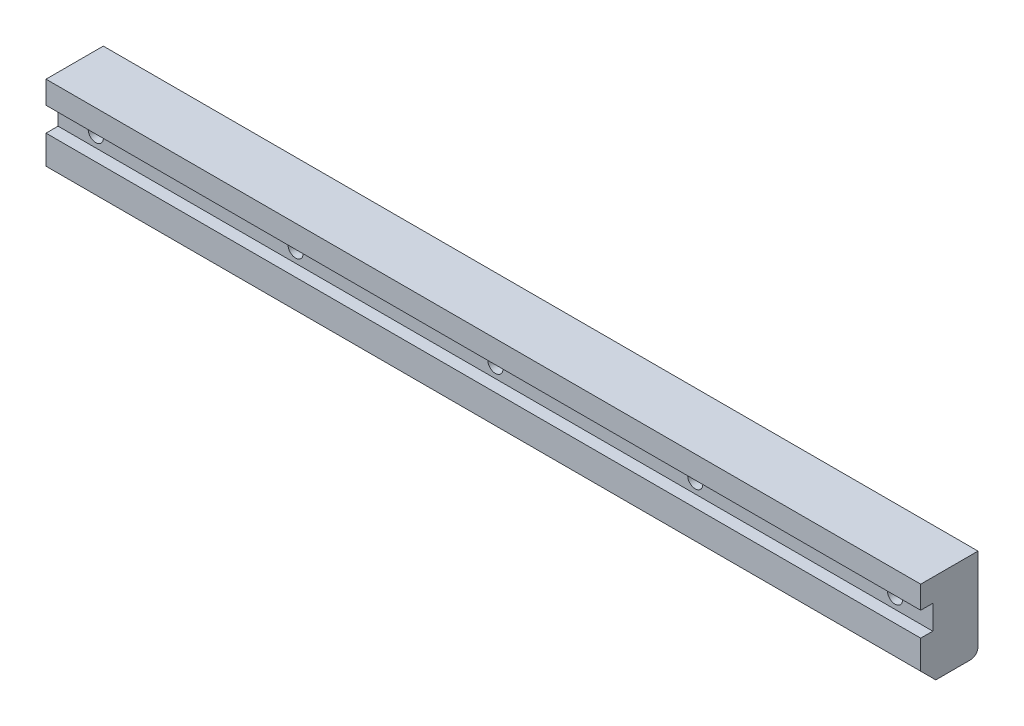
SolidWorks part; units mm, degrees
ref_plane "Alzado" through (0, 0, 0) normal (0, 0, 1) x (1, 0, 0)
ref_plane "Planta" through (0, 0, 0) normal (0, 1, 0) x (1, 0, 0)
ref_plane "Vista lateral" through (0, 0, 0) normal (1, 0, 0) x (0, 0, -1)
sketch "Croquis1" plane through (0, 0, 0) normal (1, 0, 0) x (0, 0, -1)
  line L0 (10, 0) -> (0, 10)
  line L1 (0, 10) -> (0, 29)
  line L2 (0, 29) -> (8, 29)
  line L3 (8, 29) -> (8, 45)
  line L4 (8, 45) -> (0, 45)
  line L5 (0, 45) -> (0, 60)
  line L6 (0, 60) -> (38, 60)
  line L7 (10, 0) -> (38, 0)
  line L8 (38, 0) -> (38, 60)
  point P2 (19, 60)
  point P12 (38, 63.2629)
  dimension "D1" = 10
  dimension "D2" = 16
  dimension "D3" = 15
  dimension "D4" = 60
  dimension "D5" = 28
  dimension "D6" = 8
  dimension "D7" = 45
extrude "Saliente-Extruir1" add sketch "Croquis1" along normal blind 580
fillet "Redondeo1" radius 5 1 edges at (290, 0, -38)
sketch "Croquis2" plane through (0, 0, -8) normal (0, 0, 1) x (1, 0, 0)
  line L2 (0, 37) -> (580, 37) construction
  line L3 (0, 45) -> (0, 29) construction
  line L4 (580, 45) -> (580, 29) construction
  circle A0 centre (25, 37) radius 5
  circle A1 centre (157.5, 37) radius 5
  circle A2 centre (555, 37) radius 5
  circle A3 centre (290, 37) radius 5
  circle A4 centre (422.5, 37) radius 5
  point P14 (203.3206, 37)
  point P17 (517.153, 29)
  point P18 (426.9641, 37)
  dimension "D1" = 10
  dimension "D3" = 132.5
  dimension "D4" = 132.5
  dimension "D5" = 132.5
  dimension "D6" = 132.5
  dimension "D2" = 25
extrude "Cortar-Extruir1" cut sketch "Croquis2" against normal up to next
